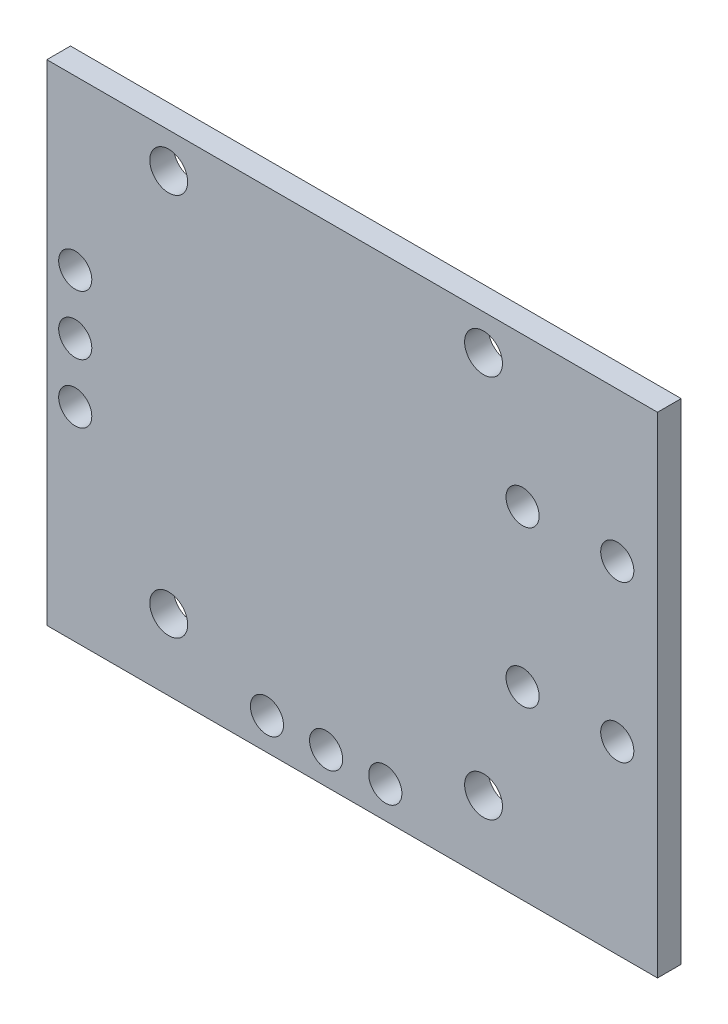
SolidWorks part; units mm, degrees
ref_plane "正面" through (0, 0, 0) normal (0, 0, 1) x (1, 0, 0)
ref_plane "平面" through (0, 0, 0) normal (0, 1, 0) x (1, 0, 0)
ref_plane "右側面" through (0, 0, 0) normal (1, 0, 0) x (0, 0, -1)
sketch "ｽｹｯﾁ1" plane through (0, 0, 0) normal (0, 0, 1) x (1, 0, 0)
  line L0 (0, -9.6) -> (25.8, -9.6) construction
  line L1 (0, 0) -> (25.8, 0)
  line L2 (0, 0) -> (0, -20.7)
  line L3 (0, -20.7) -> (25.8, -20.7)
  line L4 (25.8, 0) -> (25.8, -20.7)
  line L5 (1.2, -20.7) -> (1.2, 0) construction
  line L6 (25.8, -1.5) -> (0, -1.5) construction
  line L7 (20.1, -6.3) -> (24.1, -6.3) construction
  line L8 (20.1, -6.3) -> (20.1, -12.9) construction
  line L9 (20.1, -12.9) -> (24.1, -12.9) construction
  line L10 (24.1, -6.3) -> (24.1, -12.9) construction
  line L11 (25.8, -17.7) -> (0, -17.7) construction
  line L12 (18.45, -20.7) -> (18.45, 0) construction
  line L13 (5.15, 0) -> (5.15, -20.7) construction
  line L14 (25.8, -12.1) -> (0, -12.1) construction
  line L15 (25.8, -7.1) -> (0, -7.1) construction
  line L16 (9.3, -19.35) -> (25.8, -19.35) construction
  line L17 (5.15, -1.5) -> (18.45, -17.7) construction
  line L18 (5.15, -17.7) -> (18.45, -1.5) construction
  line L19 (11.8, -9.6) -> (11.8, -20.7) construction
  line L21 (11.8, -9.6) -> (0, -9.6) construction
  circle A0 centre (1.2, -7.1) radius 0.7
  circle A1 centre (1.2, -9.6) radius 0.7
  circle A2 centre (1.2, -12.1) radius 0.7
  circle A3 centre (5.15, -17.7) radius 0.8
  circle A4 centre (5.15, -1.5) radius 0.8
  circle A5 centre (18.45, -1.5) radius 0.8
  circle A6 centre (18.45, -17.7) radius 0.8
  circle A7 centre (9.3, -19.35) radius 0.7
  circle A8 centre (11.8, -19.35) radius 0.7
  circle A10 centre (20.1, -6.3) radius 0.7
  circle A11 centre (24.1, -6.3) radius 0.7
  circle A12 centre (20.1, -12.9) radius 0.7
  circle A13 centre (24.1, -12.9) radius 0.7
  circle A14 centre (14.3, -19.35) radius 0.7
  dimension "D3" = 1.4
  dimension "D4" = 1.4
  dimension "D8" = 1.6
  dimension "D16" = 1.4
  dimension "D1" = 20.7
  dimension "D2" = 25.8
  dimension "D5" = 6.6
  dimension "D6" = 4
  dimension "D7" = 20.1
  dimension "D9" = 2.5
  dimension "D10" = 1.2
  dimension "D11" = 13.3
  dimension "D12" = 1.35
  dimension "D13" = 3
  dimension "D14" = 2.5
  dimension "D17" = 1.5
  dimension "D18" = 5.15
  dimension "D19" = 2.5
extrude "ﾎﾞｽ - 押し出し1" add sketch "ｽｹｯﾁ1" along normal blind 1 contours L4 L1 L2 L3 A13 A12 A11 A10 A8 A7 A6 A5 A4 A3 A2 A1 A0
